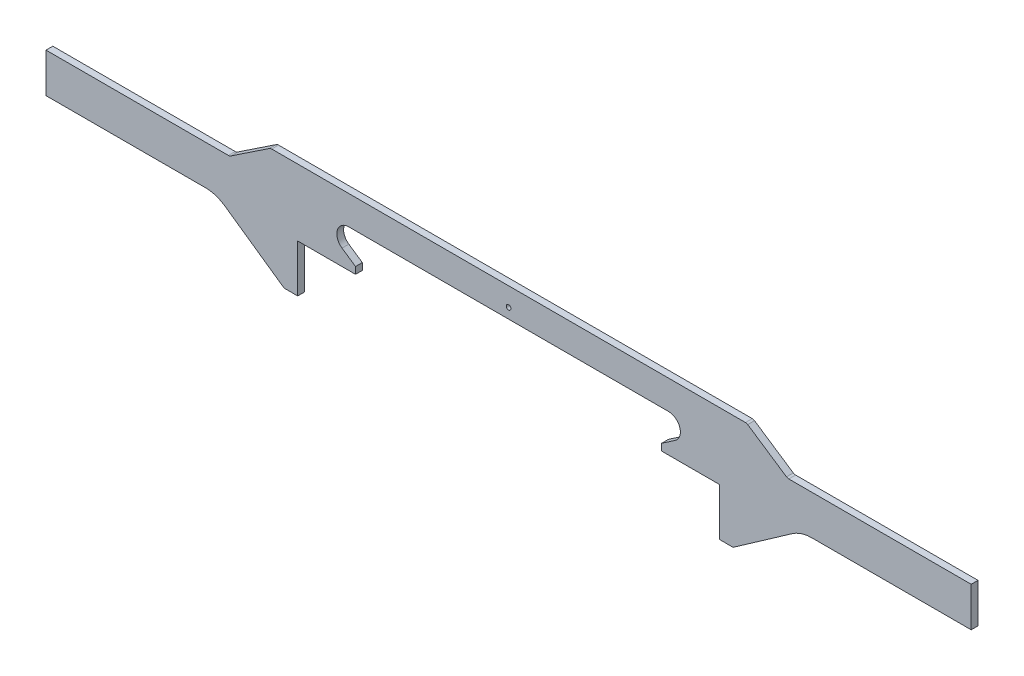
SolidWorks part; units mm, degrees
material "Q355"
ref_plane "前视基准面" through (0, 0, 0) normal (0, 0, 1) x (1, 0, 0)
ref_plane "上视基准面" through (0, 0, 0) normal (0, 1, 0) x (1, 0, 0)
ref_plane "右视基准面" through (0, 0, 0) normal (1, 0, 0) x (0, 0, -1)
sketch "草图1" plane through (0, 0, 0) normal (0, 0, 1) x (1, 0, 0)
  line L0 (-350, 0) -> (350, 0)
  line L1 (-350, 0) -> (-410, -40)
  line L2 (-410, -40) -> (-680, -40)
  line L3 (350, 0) -> (410, -40)
  line L4 (410, -40) -> (680, -40)
  line L5 (0, 0) -> (0, -60) construction
  line L6 (-680, -40) -> (-680, -98)
  line L7 (-680, -98) -> (-429.9704, -98)
  line L8 (680, -98) -> (680, -40)
  line L9 (-429.9704, -98) -> (-330, -168)
  line L10 (-330, -168) -> (-310, -168)
  line L11 (-310, -168) -> (-310, -98)
  line L12 (-310, -98) -> (-225, -98)
  line L13 (429.9704, -98) -> (330, -168)
  line L14 (330, -168) -> (310, -168)
  line L15 (310, -168) -> (310, -98)
  line L16 (310, -98) -> (225, -98)
  line L17 (-225, -98) -> (-225, -88)
  line L18 (429.9704, -98) -> (680, -98)
  line L23 (-235, -60) -> (235, -60) construction
  line L24 (-235, -42.5) -> (235, -42.5)
  line L26 (225, -98) -> (225, -88)
  line L27 (-225, -88) -> (-244.859, -74.4586)
  line L28 (225, -88) -> (244.859, -74.4586)
  arc A4 (-235, -42.5) -> (-244.859, -74.4586) centre (-235, -60) ccw
  arc A5 (244.859, -74.4586) -> (235, -42.5) centre (235, -60) ccw
  point P24 (0, -60)
  dimension "D6" = 470
  dimension "D7" = 17.5
  dimension "D2" = 40
  dimension "D3" = 60
  dimension "D4" = 700
  dimension "D5" = 58
  dimension "D8" = 60
  dimension "D9" = 145
  dimension "D10" = 620
  dimension "D11" = 98
  dimension "D12" = 85
  dimension "D13" = 20
  dimension "D14" = 10
  dimension "D15" = 168
  dimension "D16" = 1360
extrude "凸台-拉伸1" add sketch "草图1" along normal blind 10
fillet "圆角1" radius 6 4 edges at (410, -40, 5) (350, 0, 5) (-410, -40, 5) (-350, 0, 5)
hole_wizard "M8 螺纹孔1" positions "草图2" profile "草图3" tap size "M8" standard "GB"
sketch "草图2" plane through (0, 0, 10) normal (0, 0, 1) x (1, 0, 0)
  line L0 (-235, -42.5) -> (235, -42.5) construction
  line L1 (0, 0) -> (0, -27.5) construction
  point P0 (0, -27.5)
  dimension "D1" = 15
sketch "草图3" plane through (0, -27.5, 10) normal (1, 0, 0) x (0, -1, 0)
  line L0 (0, 0) -> (0, 21.7929)
  line L1 (0, 21.7929) -> (3.4, 19.75)
  line L2 (3.4, 19.75) -> (3.4, 0)
  line L5 (3.4, 0) -> (0, 0)
  line L10 (0, 21.7929) -> (-3.4, 19.75) construction
  line L11 (0, -6.35) -> (0, 107.95) construction
  dimension "螺纹孔钻头直径" = 6.8
  dimension "螺纹孔钻头深度" = 19.75
  dimension "导头角度" = 118
cosmetic thread "孔螺蚊线1" parameters "D1"=10, "D2"=8
fillet "圆角2" radius 50 2 edges at (429.9704, -98, 5) (-429.9704, -98, 5)
